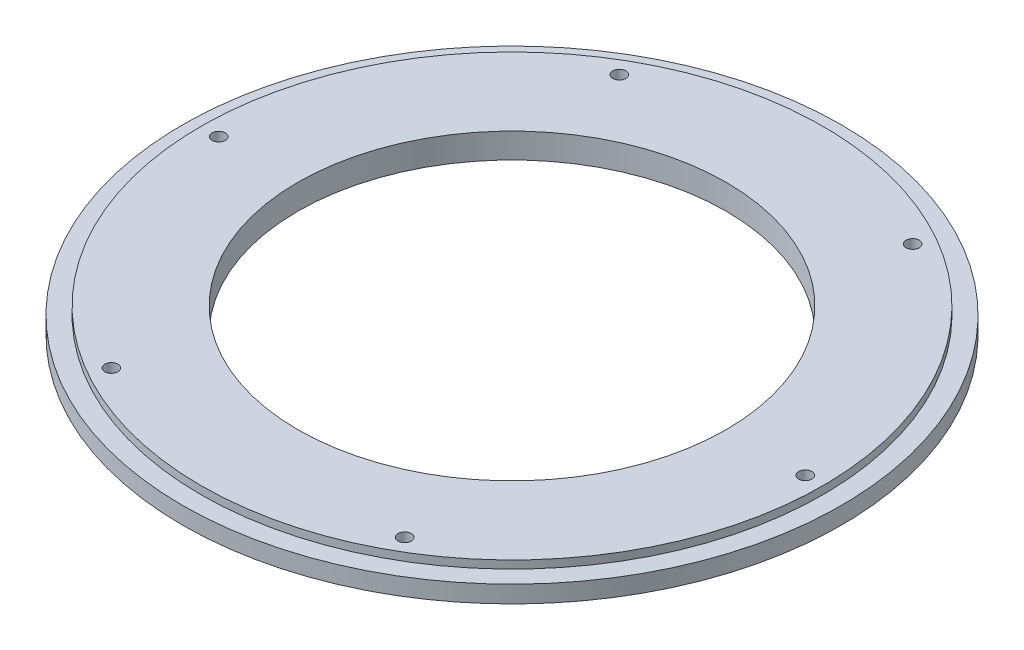
SolidWorks part; units mm, degrees
material "Pine"
ref_plane "Front Plane" through (0, 0, 0) normal (0, 0, 1) x (1, 0, 0)
ref_plane "Top Plane" through (0, 0, 0) normal (0, 1, 0) x (1, 0, 0)
ref_plane "Right Plane" through (0, 0, 0) normal (1, 0, 0) x (0, 0, -1)
sketch "Sketch1" plane through (0, 0, 0) normal (0, 1, 0) x (1, 0, 0)
  circle A0 centre (0, 0) radius 250
  circle A1 centre (0, 0) radius 162.5
  dimension "D1" = 325
  dimension "D2" = 500
extrude "Boss-Extrude1" add sketch "Sketch1" along normal blind 19
sketch "Sketch2" plane through (0, 19, 0) normal (0, 1, 0) x (1, 0, 0)
  circle A0 centre (0, 0) radius 236
  circle A1 centre (0, 0) radius 250
  dimension "D1" = 472
  dimension "D2" = 500
extrude "Cut-Extrude1" cut sketch "Sketch2" against normal blind 6
sketch "Sketch3" plane through (0, 19, 0) normal (0, 1, 0) x (1, 0, 0)
  line L0 (-1000, 0) -> (49000, 0) construction
  line L1 (0, -1000) -> (0, 49000) construction
  line L2 (-500, -866.0254) -> (24500, 42435.2448) construction
  line L3 (-500, 866.0254) -> (24500, -42435.2448) construction
  circle A0 centre (0, 0) radius 222.5 construction
  circle A1 centre (111.25, 192.6907) radius 5
  circle A3 centre (111.25, -192.6907) radius 5
  circle A5 centre (-111.25, -192.6907) radius 5
  circle A6 centre (222.5, 0) radius 5
  circle A7 centre (-111.25, 192.6907) radius 5
  circle A8 centre (-222.5, 0) radius 5
  dimension "D1" = 10
  dimension "D2" = 10
  dimension "D3" = 445
  dimension "D4" = 222.5
  dimension "D5" = 222.5
  dimension "D6" = 10
  dimension "D7" = 60
extrude "Cut-Extrude2" cut sketch "Sketch3" against normal through all
